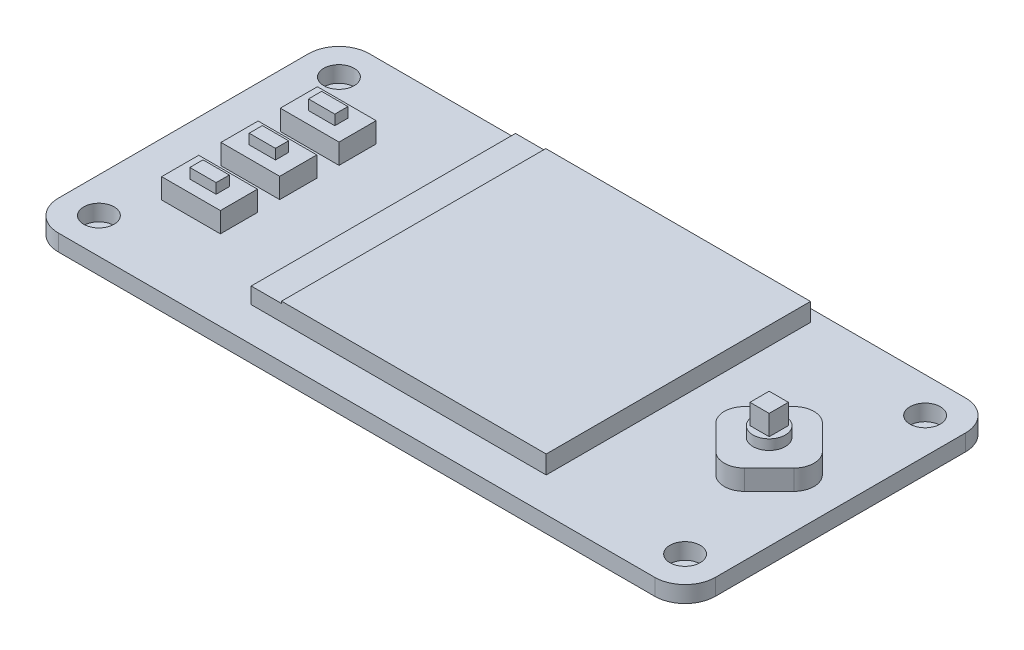
SolidWorks part; units mm, degrees
ref_plane "前视基准面" through (0, 0, 0) normal (0, 0, 1) x (1, 0, 0)
ref_plane "上视基准面" through (0, 0, 0) normal (0, 1, 0) x (1, 0, 0)
ref_plane "右视基准面" through (0, 0, 0) normal (1, 0, 0) x (0, 0, -1)
sketch "草图1" plane through (0, 0, 0) normal (0, 1, 0) x (1, 0, 0)
  line L1 (-29.5, 15.375) -> (29.5, 15.375)
  line L2 (-32.5, 12.375) -> (-32.5, -12.375)
  line L3 (-29.5, -15.375) -> (29.5, -15.375)
  line L4 (32.5, 12.375) -> (32.5, -12.375)
  line L5 (-32.5, 15.375) -> (32.5, -15.375) construction
  line L6 (-32.5, -15.375) -> (32.5, 15.375) construction
  arc A0 (-32.5, -12.375) -> (-29.5, -15.375) centre (-29.5, -12.375) ccw
  arc A1 (29.5, -15.375) -> (32.5, -12.375) centre (29.5, -12.375) ccw
  arc A2 (29.5, 15.375) -> (32.5, 12.375) centre (29.5, 12.375) cw
  arc A3 (-29.5, 15.375) -> (-32.5, 12.375) centre (-29.5, 12.375) ccw
  point P0 (0, 0)
  dimension "D3" = 3
  dimension "D1" = 30.75
  dimension "D2" = 65
extrude "凸台-拉伸1" add sketch "草图1" along normal blind 1.63
sketch "草图2" plane through (0, 1.63, 0) normal (0, 1, 0) x (1, 0, 0)
  line L0 (29.5, 15.375) -> (-29.5, 15.375) construction
  line L2 (-32.5, 12.375) -> (-32.5, -12.375) construction
  line L3 (-29.5, -15.375) -> (29.5, -15.375) construction
  line L4 (32.5, -12.375) -> (32.5, 12.375) construction
  circle A0 centre (-29, 11.875) radius 1.5
  circle A1 centre (-29, -11.875) radius 1.5
  circle A2 centre (29, -11.875) radius 1.5
  circle A3 centre (29, 11.875) radius 1.5
  dimension "D1" = 3
  dimension "D2" = 3.5
  dimension "D3" = 3.5
  dimension "D4" = 3.5
  dimension "D5" = 3.5
extrude "切除-拉伸1" cut sketch "草图2" against normal blind 1.6
sketch "草图3" plane through (0, 1.63, 0) normal (0, 1, 0) x (1, 0, 0)
  line L0 (-29.5, -15.375) -> (29.5, -15.375) construction
  line L1 (-13.83, 14.175) -> (15.36, 14.175)
  line L2 (-13.83, 14.175) -> (-13.83, -11.975)
  line L3 (-13.83, -11.975) -> (15.36, -11.975)
  line L4 (15.36, 14.175) -> (15.36, -11.975)
  line L7 (32.5, -12.375) -> (32.5, 12.375) construction
  dimension "D1" = 26.15
  dimension "D2" = 29.19
  dimension "D3" = 3.4
  dimension "D4" = 17.14
sketch "草图4" plane through (0, 1.63, 0) normal (0, 1, 0) x (1, 0, 0)
  line L0 (-29.5, -15.375) -> (29.5, -15.375) construction
  line L1 (-27.23, 7.975) -> (-21.42, 7.975)
  line L2 (-27.23, 7.975) -> (-27.23, 4.305)
  line L3 (-27.23, 4.305) -> (-21.42, 4.305)
  line L4 (-21.42, 7.975) -> (-21.42, 4.305)
  line L5 (-27.23, 2.105) -> (-21.42, 2.105)
  line L6 (-27.23, 2.105) -> (-27.23, -1.565)
  line L7 (-27.23, -1.565) -> (-21.42, -1.565)
  line L8 (-21.42, 2.105) -> (-21.42, -1.565)
  line L9 (-27.23, -3.765) -> (-21.42, -3.765)
  line L10 (-27.23, -3.765) -> (-27.23, -7.435)
  line L11 (-27.23, -7.435) -> (-21.42, -7.435)
  line L12 (-21.42, -3.765) -> (-21.42, -7.435)
  line L13 (-32.5, 12.375) -> (-32.5, -12.375) construction
  dimension "D1" = 5.81
  dimension "D2" = 3.67
  dimension "D3" = 2.2
  dimension "D4" = 2.2
  dimension "D5" = 7.94
  dimension "D6" = 5.27
sketch "草图5" plane through (0, 1.63, 0) normal (0, 1, 0) x (1, 0, 0)
  line L0 (26.5747, 4.1383) -> (29.0142, 1.6987)
  line L1 (23.7463, 4.1383) -> (21.3067, 1.6987)
  line L2 (29.0142, -1.1297) -> (26.5747, -3.5692)
  line L3 (21.3067, -1.1297) -> (23.7463, -3.5692)
  line L4 (32.5, -12.375) -> (32.5, 12.375) construction
  line L5 (-29.5, -15.375) -> (29.5, -15.375) construction
  arc A0 (26.5747, -3.5692) -> (23.7463, -3.5692) centre (25.1605, -2.155) cw
  arc A1 (21.3067, 1.6987) -> (21.3067, -1.1297) centre (22.721, 0.2845) ccw
  arc A2 (23.7463, 4.1383) -> (26.5747, 4.1383) centre (25.1605, 2.724) cw
  arc A3 (29.0142, 1.6987) -> (29.0142, -1.1297) centre (27.6, 0.2845) cw
  point P8 (19.8925, 0.2845)
  point P11 (25.1605, 5.5525)
  point P14 (30.4284, 0.2845)
  point P15 (29.6, 0.2845)
  point P18 (25.1605, -4.155)
  dimension "D3" = 2
  dimension "D1" = 7.45
  dimension "D2" = 7.45
  dimension "D4" = 2.9
  dimension "D5" = 11.22
extrude "凸台-拉伸2" add sketch "草图3" along normal blind 1.8
extrude "凸台-拉伸3" add sketch "草图5" along normal blind 2
sketch "草图6" plane through (0, 3.43, 0) normal (0, 1, 0) x (1, 0, 0)
  line L0 (-13.83, -11.975) -> (15.36, -11.975) construction
  line L1 (-13.83, 14.175) -> (-10.83, 14.175)
  line L2 (-13.83, 14.175) -> (-13.83, -11.975)
  line L3 (-13.83, -11.975) -> (-10.83, -11.975)
  line L4 (-10.83, 14.175) -> (-10.83, -11.975)
  dimension "D1" = 3
extrude "切除-拉伸2" cut sketch "草图6" against normal blind 0.2
extrude "凸台-拉伸4" add sketch "草图4" along normal blind 2
sketch "草图7" plane through (0, 3.63, 0) normal (0, 1, 0) x (1, 0, 0)
  line L0 (-21.42, 7.975) -> (-27.23, 7.975) construction
  line L1 (-25.625, 6.79) -> (-23.025, 6.79)
  line L2 (-25.625, 6.79) -> (-25.625, 5.49)
  line L3 (-25.625, 5.49) -> (-23.025, 5.49)
  line L4 (-23.025, 6.79) -> (-23.025, 5.49)
  line L5 (-25.625, 6.79) -> (-23.025, 5.49) construction
  line L6 (-25.625, 5.49) -> (-23.025, 6.79) construction
  line L7 (-25.625, 0.92) -> (-23.025, 0.92)
  line L8 (-25.625, 0.92) -> (-25.625, -0.38)
  line L9 (-25.625, -0.38) -> (-23.025, -0.38)
  line L10 (-23.025, 0.92) -> (-23.025, -0.38)
  line L11 (-25.625, 0.92) -> (-23.025, -0.38) construction
  line L12 (-25.625, -0.38) -> (-23.025, 0.92) construction
  line L13 (-25.625, -4.95) -> (-23.025, -4.95)
  line L14 (-25.625, -4.95) -> (-25.625, -6.25)
  line L15 (-25.625, -6.25) -> (-23.025, -6.25)
  line L16 (-23.025, -4.95) -> (-23.025, -6.25)
  line L17 (-25.625, -4.95) -> (-23.025, -6.25) construction
  line L18 (-25.625, -6.25) -> (-23.025, -4.95) construction
  line L19 (-27.23, -3.765) -> (-27.23, -7.435) construction
  line L20 (-27.23, 2.105) -> (-27.23, -1.565) construction
  line L21 (-27.23, 7.975) -> (-27.23, 4.305) construction
  point P0 (-24.325, 6.14)
  point P5 (-24.325, 0.27)
  point P10 (-24.325, -5.6)
  point P18 (-24.325, 7.975)
  point P22 (-27.23, -5.6)
  point P26 (-27.23, 0.27)
  point P30 (-27.23, 6.14)
  dimension "D1" = 2.6
  dimension "D2" = 1.3
extrude "凸台-拉伸5" add sketch "草图7" along normal blind 1
sketch "草图8" plane through (0, 0, 0) normal (0, -1, 0) x (1, 0, 0)
  line L0 (29.5, -15.375) -> (-29.5, -15.375) construction
  line L1 (-25.7, -8.735) -> (25.3, -8.735)
  line L2 (-25.7, -8.735) -> (-25.7, -13.735)
  line L3 (-25.7, -13.735) -> (25.3, -13.735)
  line L4 (25.3, -8.735) -> (25.3, -13.735)
  line L5 (32.5, 12.375) -> (32.5, -12.375) construction
  dimension "D1" = 5
  dimension "D2" = 51
  dimension "D3" = 1.64
  dimension "D4" = 7.2
extrude "凸台-拉伸6" add sketch "草图8" along normal blind 3.68
sketch "草图9" plane through (0, 3.63, 0) normal (0, 1, 0) x (1, 0, 0)
  line L1 (24.2105, 1.2345) -> (26.1105, 1.2345)
  line L2 (24.2105, 1.2345) -> (24.2105, -0.6655)
  line L3 (24.2105, -0.6655) -> (26.1105, -0.6655)
  line L4 (26.1105, 1.2345) -> (26.1105, -0.6655)
  line L5 (24.2105, 1.2345) -> (26.1105, -0.6655) construction
  line L6 (24.2105, -0.6655) -> (26.1105, 1.2345) construction
  arc A0 (29.0142, -1.1297) -> (29.0142, 1.6987) centre (27.6, 0.2845) ccw construction
  arc A1 (26.5747, 4.1383) -> (23.7463, 4.1383) centre (25.1605, 2.724) ccw construction
  point P0 (25.1605, 0.2845)
  point P11 (29.6, 0.2845)
  point P16 (25.1605, 4.724)
  dimension "D1" = 1.9
extrude "凸台-拉伸7" add sketch "草图9" along normal blind 3
sketch "草图10" plane through (0, 3.63, 0) normal (0, 1, 0) x (1, 0, 0)
  line L0 (26.1105, 1.2345) -> (24.2105, 1.2345) construction
  line L2 (26.1105, -0.6655) -> (26.1105, 1.2345) construction
  circle A0 centre (25.1605, 0.2845) radius 1.6
  point P5 (25.1605, 1.2345)
  point P11 (26.1105, 0.2845)
  dimension "D1" = 3.2
extrude "凸台-拉伸8" add sketch "草图10" along normal blind 1
